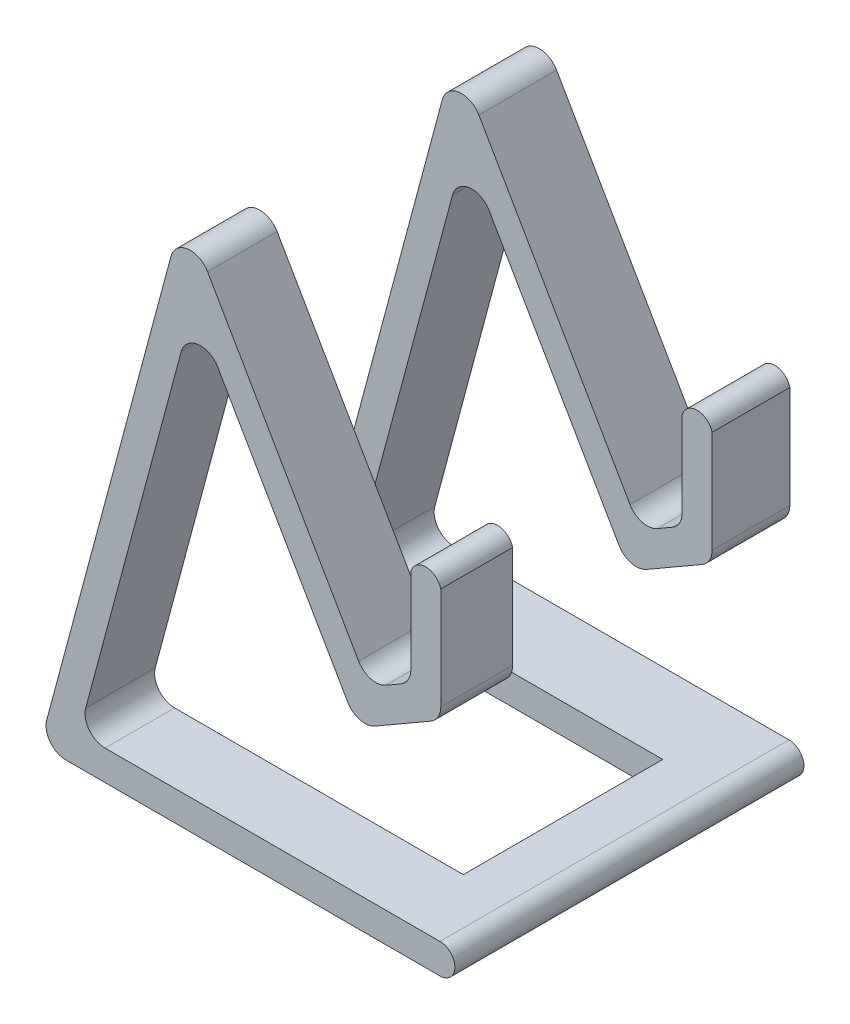
SolidWorks part; units mm, degrees
ref_plane "Front Plane" through (0, 0, 0) normal (0, 0, 1) x (1, 0, 0)
ref_plane "Top Plane" through (0, 0, 0) normal (0, 1, 0) x (1, 0, 0)
ref_plane "Right Plane" through (0, 0, 0) normal (1, 0, 0) x (0, 0, -1)
sketch "Sketch1" plane through (0, 0, 0) normal (0, 0, 1) x (1, 0, 0)
  line L5 (0, 3) -> (-67.1569, 3)
  line L6 (-71.0206, 8.0353) -> (-51.8737, 79.4925)
  line L7 (-44.5459, 80.4572) -> (-18.4956, 35.3368)
  line L8 (-13.0315, 33.8727) -> (-1.8282, 40.341)
  line L9 (0.1718, 43.8051) -> (0.1718, 64.2918)
  line L10 (0, -3) -> (-74.9762, -3)
  line L11 (-78.8399, 2.0353) -> (-53.9202, 95.0371)
  line L12 (-46.5924, 96.0018) -> (-16.2995, 43.533)
  line L13 (-10.8354, 42.0689) -> (-7.8282, 43.8051)
  line L14 (-5.8282, 47.2692) -> (-5.8282, 64.2918)
  arc A0 (0, 3) -> (0, -3) centre (0, 0) cw
  arc A1 (-5.8282, 64.2918) -> (0.1718, 64.2918) centre (-2.8282, 63.5299) cw
  arc A2 (-53.9202, 95.0371) -> (-46.5924, 96.0018) centre (-50.0565, 94.0018) cw
  arc A3 (-51.8737, 79.4925) -> (-44.5459, 80.4572) centre (-48.01, 78.4572) cw
  arc A4 (-67.1569, 3) -> (-71.0206, 8.0353) centre (-67.1569, 7) cw
  arc A5 (-74.9762, -3) -> (-78.8399, 2.0353) centre (-74.9762, 1) cw
  arc A6 (-1.8282, 40.341) -> (0.1718, 43.8051) centre (-3.8282, 43.8051) ccw
  arc A7 (-7.8282, 43.8051) -> (-5.8282, 47.2692) centre (-9.8282, 47.2692) ccw
  arc A8 (-16.2995, 43.533) -> (-10.8354, 42.0689) centre (-12.8354, 45.533) ccw
  arc A9 (-18.4956, 35.3368) -> (-13.0315, 33.8727) centre (-15.0315, 37.3368) ccw
  point P21 (0, 0)
  dimension "D1" = 4
  dimension "D2" = 4
extrude "Boss-Extrude1" add sketch "Sketch1" along normal blind 70
sketch "Sketch2" plane through (0, 0, 0) normal (1, 0, 0) x (0, 0, -1)
  line L1 (-55.5888, 12.2372) -> (-15.5888, 12.2372)
  line L2 (-55.5888, 12.2372) -> (-55.5888, 102.2372)
  line L3 (-55.5888, 102.2372) -> (-15.5888, 102.2372)
  line L4 (-15.5888, 12.2372) -> (-15.5888, 102.2372)
  line L5 (-55.5888, 12.2372) -> (-15.5888, 102.2372) construction
  line L6 (-55.5888, 102.2372) -> (-15.5888, 12.2372) construction
  point P0 (-35.5888, 57.2372)
  point P7 (0, 0)
  point P8 (0, 0)
  point P9 (0, 0)
  dimension "D1" = 40
  dimension "D2" = 90
extrude "Cut-Extrude3" cut sketch "Sketch2" against normal through all both and the other way through all
sketch "Sketch3" plane through (0, 0, 0) normal (0, 1, 0) x (1, 0, 0)
  line L1 (-83.4544, -16.0517) -> (-9.2541, -16.0517)
  line L2 (-83.4544, -16.0517) -> (-83.4544, -56.0517)
  line L3 (-83.4544, -56.0517) -> (-9.2541, -56.0517)
  line L4 (-9.2541, -16.0517) -> (-9.2541, -56.0517)
  line L5 (-83.4544, -16.0517) -> (-9.2541, -56.0517) construction
  line L6 (-83.4544, -56.0517) -> (-9.2541, -16.0517) construction
  point P0 (-46.3543, -36.0517)
  dimension "D1" = 40
extrude "Cut-Extrude4" cut sketch "Sketch3" against normal through all both and the other way through all
